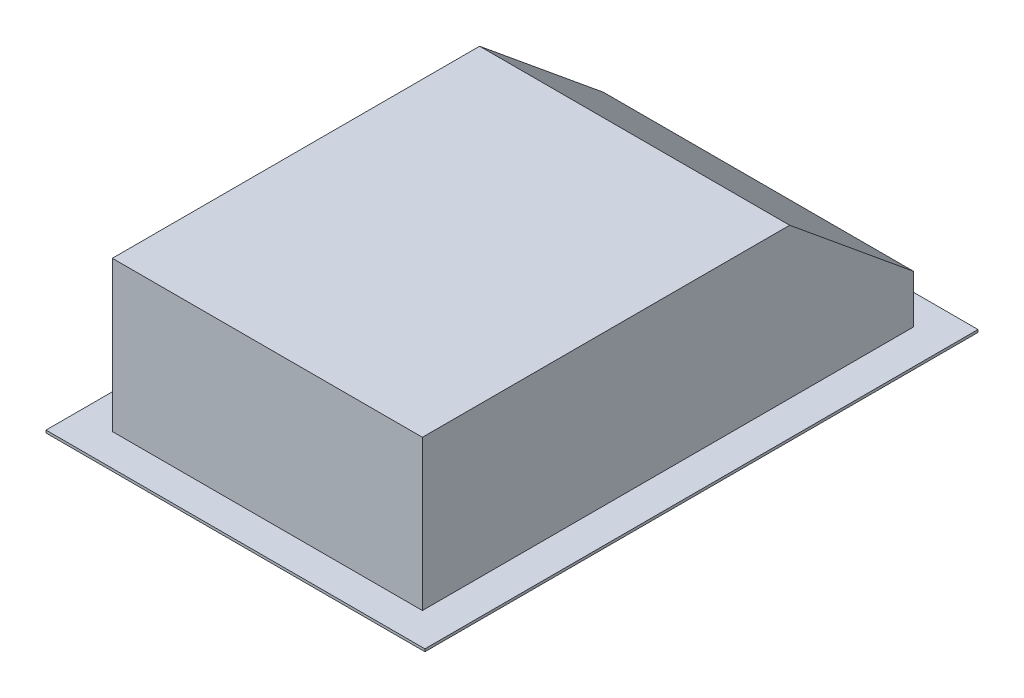
SolidWorks part; units mm, degrees
material "6061-T6 (SS)"
ref_plane "Front Plane" through (0, 0, 0) normal (0, 0, 1) x (1, 0, 0)
ref_plane "Top Plane" through (0, 0, 0) normal (0, 1, 0) x (1, 0, 0)
ref_plane "Right Plane" through (0, 0, 0) normal (1, 0, 0) x (0, 0, -1)
sketch "Sketch1" plane through (0, 0, 0) normal (0, 1, 0) x (1, 0, 0)
  line L1 (0, 0) -> (45.6, 0)
  line L2 (0, 0) -> (0, 430.25)
  line L3 (0, 430.25) -> (45.6, 430.25)
  line L4 (382.3, 0) -> (382.3, 430.25)
  line L5 (385.5, -3.2) -> (385.5, 432.75)
  line L6 (-3.2, -3.2) -> (385.5, -3.2)
  line L7 (-3.2, -3.2) -> (-3.2, 432.75)
  line L8 (-3.2, 433.45) -> (385.5, 433.45) construction
  line L9 (-3.2, 432.75) -> (385.5, 432.75)
  line L10 (45.6, 430.25) -> (45.6, 0)
  line L11 (-3.2, -3.2) -> (-3.2, 433.45) construction
  line L12 (385.5, -3.2) -> (385.5, 433.45) construction
  line L13 (48.1, 0) -> (48.1, 430.25)
  line L14 (48.1, 430.25) -> (93.7, 430.25)
  line L15 (48.1, 0) -> (93.7, 0)
  line L16 (0, 430.25) -> (382.3, 430.25) construction
  line L17 (93.7, 430.25) -> (93.7, 0)
  line L18 (0, 0) -> (382.3, 0) construction
  line L19 (96.2, 0) -> (96.2, 430.25)
  line L20 (141.8, 430.25) -> (141.8, 0)
  line L21 (144.3, 0) -> (144.3, 430.25)
  line L22 (189.9, 430.25) -> (189.9, 0)
  line L23 (192.4, 0) -> (192.4, 430.25)
  line L24 (238, 430.25) -> (238, 0)
  line L25 (240.5, 0) -> (240.5, 430.25)
  line L26 (286.1, 430.25) -> (286.1, 0)
  line L27 (288.6, 0) -> (288.6, 430.25)
  line L28 (334.2, 430.25) -> (334.2, 0)
  line L29 (336.7, 0) -> (336.7, 430.25)
  line L30 (96.2, 430.25) -> (141.8, 430.25)
  line L31 (144.3, 430.25) -> (189.9, 430.25)
  line L32 (96.2, 0) -> (141.8, 0)
  line L33 (144.3, 0) -> (189.9, 0)
  line L34 (192.4, 0) -> (238, 0)
  line L35 (240.5, 0) -> (286.1, 0)
  line L36 (288.6, 0) -> (334.2, 0)
  line L37 (336.7, 0) -> (382.3, 0)
  line L38 (192.4, 430.25) -> (238, 430.25)
  line L39 (240.5, 430.25) -> (286.1, 430.25)
  line L40 (288.6, 430.25) -> (334.2, 430.25)
  line L41 (336.7, 430.25) -> (382.3, 430.25)
  dimension "D1" = 430.25
  dimension "D2" = 382.3
  dimension "D4" = 2.5
  dimension "D3" = 3.2
  dimension "D5" = 2.5
  dimension "D6" = 45.6
  dimension "D8" = 45.6
  dimension "D7" = 7
extrude "Boss-Extrude1" add sketch "Sketch1" along normal blind 189
sketch "Sketch2" plane through (0, 0, 3.2) normal (0, 0, 1) x (1, 0, 0)
  line L0 (385.5, 189) -> (385.5, 0) construction
  line L1 (-3.2, 0) -> (385.5, 0)
  line L2 (-3.2, 0) -> (-3.2, 3.2)
  line L3 (-3.2, 3.2) -> (385.5, 3.2)
  line L4 (385.5, 0) -> (385.5, 3.2)
  dimension "D1" = 3.2
extrude "Boss-Extrude2" add sketch "Sketch2" against normal through all
sketch "Sketch3" plane through (0, 189, 0) normal (0, 1, 0) x (1, 0, 0)
  line L0 (0, 430.25) -> (0, 432.75)
  line L1 (385.5, 432.75) -> (-3.2, 432.75) construction
  line L2 (0, 432.75) -> (382.3, 432.75)
  line L3 (382.3, 430.25) -> (382.3, 432.75)
  line L4 (382.3, 430.25) -> (336.7, 430.25)
  line L5 (336.7, 430.25) -> (336.7, 0)
  line L6 (336.7, 0) -> (334.2, 0)
  line L7 (334.2, 0) -> (334.2, 430.25) construction
  line L8 (334.2, 0) -> (334.2, 430.25) construction
  line L9 (334.2, 0) -> (334.2, 430.25)
  line L10 (334.2, 430.25) -> (288.6, 430.25)
  line L11 (288.6, 430.25) -> (288.6, 0)
  line L12 (288.6, 0) -> (286.1, 0)
  line L13 (286.1, 0) -> (286.1, 430.25)
  line L14 (286.1, 430.25) -> (240.5, 430.25)
  line L15 (240.5, 430.25) -> (240.5, 0)
  line L16 (240.5, 0) -> (238, 0)
  line L17 (238, 0) -> (238, 430.25)
  line L18 (238, 430.25) -> (192.4, 430.25)
  line L19 (192.4, 430.25) -> (192.4, 0)
  line L20 (192.4, 0) -> (189.9, 0)
  line L21 (189.9, 0) -> (189.9, 430.25)
  line L22 (189.9, 430.25) -> (144.3, 430.25)
  line L23 (144.3, 430.25) -> (144.3, 0)
  line L24 (144.3, 0) -> (141.8, 0)
  line L25 (141.8, 0) -> (141.8, 430.25)
  line L26 (141.8, 430.25) -> (96.2, 430.25)
  line L27 (96.2, 430.25) -> (96.2, 0)
  line L28 (96.2, 0) -> (93.7, 0)
  line L29 (93.7, 0) -> (93.7, 430.25)
  line L30 (93.7, 430.25) -> (48.1, 430.25)
  line L31 (48.1, 430.25) -> (48.1, 0)
  line L32 (48.1, 0) -> (45.6, 0)
  line L33 (45.6, 0) -> (45.6, 430.25)
  line L34 (45.6, 430.25) -> (0, 430.25)
extrude "Cut-Extrude1" cut sketch "Sketch3" against normal blind 25
sketch "Sketch4" plane through (385.5, 0, 0) normal (1, 0, 0) x (0, 0, -1)
  line L0 (432.75, 189) -> (662.75, 0)
  line L1 (432.75, 0) -> (662.75, 0)
  line L2 (432.75, 0) -> (432.75, 189)
  dimension "D1" = 230
extrude "Boss-Extrude4" add sketch "Sketch4" against normal blind 3.2 contours L0 L1 L2
sketch "Sketch7" plane through (-3.2, 0, 0) normal (-1, 0, 0) x (0, 0, 1)
  line L0 (-432.75, 164) -> (-432.75, 189)
  line L8 (-430.25, 3.2) -> (0, 3.2)
  line L9 (0, 3.2) -> (0, 189)
  line L10 (0, 189) -> (-432.75, 189)
  line L11 (-432.75, 189) -> (-662.75, 0)
  line L12 (-662.75, 0) -> (-432.75, 0)
  line L13 (-432.75, 0) -> (-432.75, 164)
  line L14 (-432.75, 164) -> (-430.25, 164)
  line L15 (-430.25, 164) -> (-430.25, 3.2)
  line L19 (-432.75, 189) -> (-662.75, 0)
  line L20 (-662.75, 0) -> (-432.75, 0)
  line L21 (-432.75, 0) -> (-432.75, 164)
  dimension "D1" = 0
extrude "Boss-Extrude5" add sketch "Sketch7" against normal blind 3.2
sketch "Sketch9" plane through (0, 0, 0) normal (1, 0, 0) x (0, 0, -1)
  line L0 (662.75, 0) -> (658.8558, 3.2)
  line L1 (432.75, 0) -> (662.75, 0)
  line L2 (432.75, 0) -> (432.75, 3.2)
  line L3 (432.75, 3.2) -> (658.8558, 3.2)
  line L5 (432.75, 189) -> (662.75, 0) construction
  line L6 (662.75, 0) -> (432.75, 0) construction
  dimension "D1" = 3.2
extrude "Boss-Extrude6" add sketch "Sketch9" along normal up to next
sketch "Sketch11" plane through (385.5, 0, 0) normal (1, 0, 0) x (0, 0, -1)
  line L1 (662.75, 0) -> (610.16, 0)
  line L2 (662.75, 0) -> (662.75, 168.0196)
  line L3 (662.75, 168.0196) -> (610.16, 168.0196)
  line L4 (610.16, 0) -> (610.16, 168.0196)
  dimension "D1" = 52.59
extrude "Cut-Extrude2" cut sketch "Sketch11" against normal up to next
sketch "Sketch12" plane through (385.5, 0, 0) normal (1, 0, 0) x (0, 0, -1)
  line L1 (432.75, 189) -> (610.16, 43.2153) construction
  line L2 (442.2732, 200.5891) -> (619.6832, 54.8044)
  line L3 (456.3764, 189) -> (610.16, 62.63)
  line L4 (432.75, 189) -> (610.16, 43.2153)
  line L5 (432.75, 189) -> (456.3764, 189)
  line L6 (610.16, 43.2153) -> (610.16, 62.63)
  dimension "D1" = 15
extrude "Boss-Extrude7" add sketch "Sketch12" against normal blind 3.2
sketch "Sketch13" plane through (-3.2, 0, 0) normal (-1, 0, 0) x (0, 0, 1)
  line L0 (-610.16, 62.63) -> (-610.16, 3.2) construction
  line L1 (-432.75, 189) -> (-610.16, 43.2153) construction
  line L2 (0, 189) -> (-456.3764, 189) construction
  line L3 (-610.16, 62.63) -> (-456.3764, 189) construction
  line L4 (-610.16, 62.63) -> (-610.16, 43.2153)
  line L5 (-432.75, 189) -> (-610.16, 43.2153)
  line L6 (-432.75, 189) -> (-456.3764, 189)
  line L7 (-610.16, 62.63) -> (-456.3764, 189)
extrude "Boss-Extrude8" add sketch "Sketch13" against normal blind 3.2
sketch "Sketch14" plane through (0, 0, -610.16) normal (0, 0, -1) x (-1, 0, 0)
  line L0 (0, 3.2) -> (3.2, 3.2) construction
  line L1 (3.2, 0) -> (3.2, 62.63) construction
  line L2 (-382.3, 3.2) -> (-385.5, 3.2) construction
  line L3 (-385.5, 62.63) -> (-385.5, 0) construction
  line L5 (-385.5, 3.2) -> (3.2, 3.2)
  line L6 (-385.5, 3.2) -> (-385.5, 0)
  line L7 (-385.5, 0) -> (3.2, 0)
  line L8 (3.2, 3.2) -> (3.2, 0)
extrude "Boss-Extrude9" add sketch "Sketch14" along normal blind 40
sketch "Sketch15" plane through (0, 0, 3.2) normal (0, 0, 1) x (1, 0, 0)
  line L0 (385.5, 189) -> (385.5, 0) construction
  line L1 (-3.2, 0) -> (385.5, 0)
  line L2 (-3.2, 0) -> (-3.2, 3.2)
  line L3 (-3.2, 3.2) -> (385.5, 3.2)
  line L4 (385.5, 0) -> (385.5, 3.2)
  dimension "D1" = 3.2
extrude "Boss-Extrude10" add sketch "Sketch15" along normal blind 40
sketch "Sketch16" plane through (385.5, 0, 0) normal (1, 0, 0) x (0, 0, -1)
  line L1 (-43.2, 3.2) -> (650.16, 3.2)
  line L2 (-43.2, 3.2) -> (-43.2, 0)
  line L3 (-43.2, 0) -> (650.16, 0)
  line L4 (650.16, 3.2) -> (650.16, 0)
extrude "Boss-Extrude11" add sketch "Sketch16" along normal blind 43.15
sketch "Sketch17" plane through (-3.2, 0, 0) normal (-1, 0, 0) x (0, 0, 1)
  line L1 (-650.16, 3.2) -> (43.2, 3.2)
  line L2 (-650.16, 3.2) -> (-650.16, 0)
  line L3 (-650.16, 0) -> (43.2, 0)
  line L4 (43.2, 3.2) -> (43.2, 0)
extrude "Boss-Extrude12" add sketch "Sketch17" along normal blind 43.15
sketch "Sketch18" plane through (-3.2, 0, 0) normal (-1, 0, 0) x (0, 0, 1)
  line L6 (-456.3764, 189) -> (3.2, 189) construction
  line L7 (-456.3764, 189) -> (-610.16, 62.63) construction
  line L8 (-610.16, 3.2) -> (-610.16, 62.63) construction
  line L9 (-457.2002, 191.3) -> (3.2, 191.3)
  line L10 (-612.46, 63.7169) -> (-457.2002, 191.3)
  line L11 (-612.46, 3.2) -> (-612.46, 63.7169)
  line L12 (-457.2002, 191.3) -> (3.2, 191.3)
  line L13 (-612.46, 63.7169) -> (-457.2002, 191.3)
  line L14 (-612.46, 3.2) -> (-612.46, 63.7169)
  line L16 (-456.3764, 189) -> (3.2, 189)
  line L17 (-456.3764, 189) -> (-610.16, 62.63)
  line L18 (-610.16, 3.2) -> (-610.16, 62.63)
  line L19 (-612.46, 3.2) -> (-610.16, 3.2)
  line L20 (3.2, 189) -> (3.2, 191.3)
  dimension "D1" = 2.3
extrude "Boss-Extrude13" add sketch "Sketch18" against normal up to surface (388.7 mm away) up to face at (385.5, 89.406, -334.0593)
ref_plane "Plane1" through (191.15, 0, 0) normal (-1, 0, 0) x (0, 0, 1)
ref_plane "Plane2" through (0, 0, -304.63) normal (0, 0, -1) x (-1, 0, 0)
